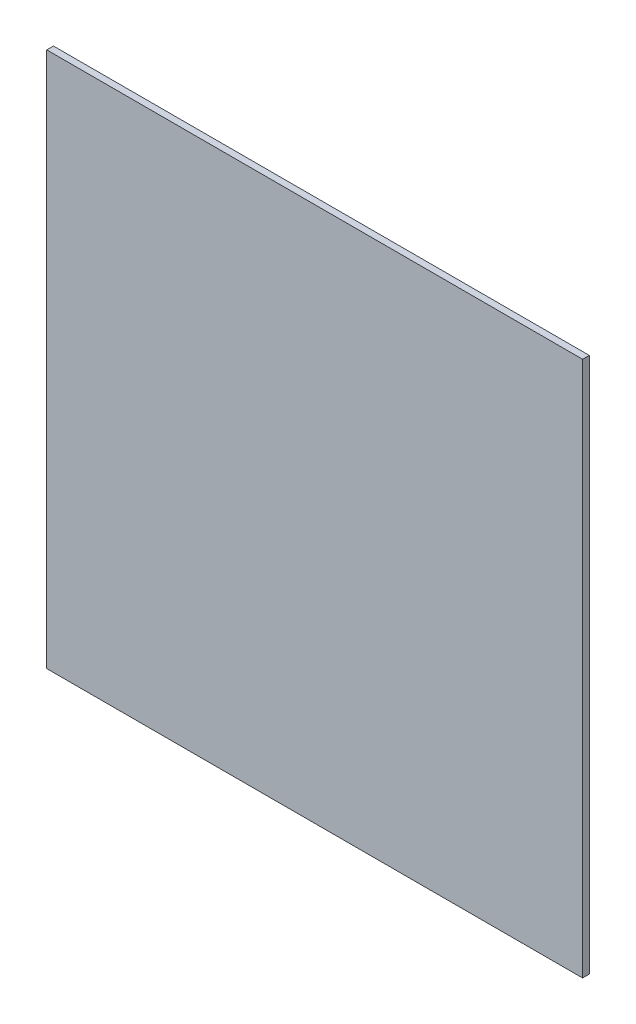
SolidWorks part; units mm, degrees
ref_plane "Front Plane" through (0, 0, 0) normal (0, 0, 1) x (1, 0, 0)
ref_plane "Top Plane" through (0, 0, 0) normal (0, 1, 0) x (1, 0, 0)
ref_plane "Right Plane" through (0, 0, 0) normal (1, 0, 0) x (0, 0, -1)
sketch "Sketch1" plane through (0, 0, 0) normal (0, 0, 1) x (1, 0, 0)
  line L1 (-69.0767, 47.3734) -> (83.3233, 47.3734)
  line L2 (-69.0767, 47.3734) -> (-69.0767, -105.0266)
  line L3 (-69.0767, -105.0266) -> (83.3233, -105.0266)
  line L4 (83.3233, 47.3734) -> (83.3233, -105.0266)
  line L5 (-56.3767, 34.6734) -> (70.6233, 34.6734)
  line L6 (-56.3767, 34.6734) -> (-56.3767, -92.3266)
  line L7 (-56.3767, -92.3266) -> (70.6233, -92.3266)
  line L8 (70.6233, 34.6734) -> (70.6233, -92.3266)
  dimension "D1" = 152.4
  dimension "D2" = 152.4
  dimension "D3" = 12.7
  dimension "D4" = 127
  dimension "D5" = 12.7
  dimension "D6" = 127
extrude "Boss-Extrude1" add sketch "Sketch1" along normal blind 1.5875 contours L8 L5 L6 L7
